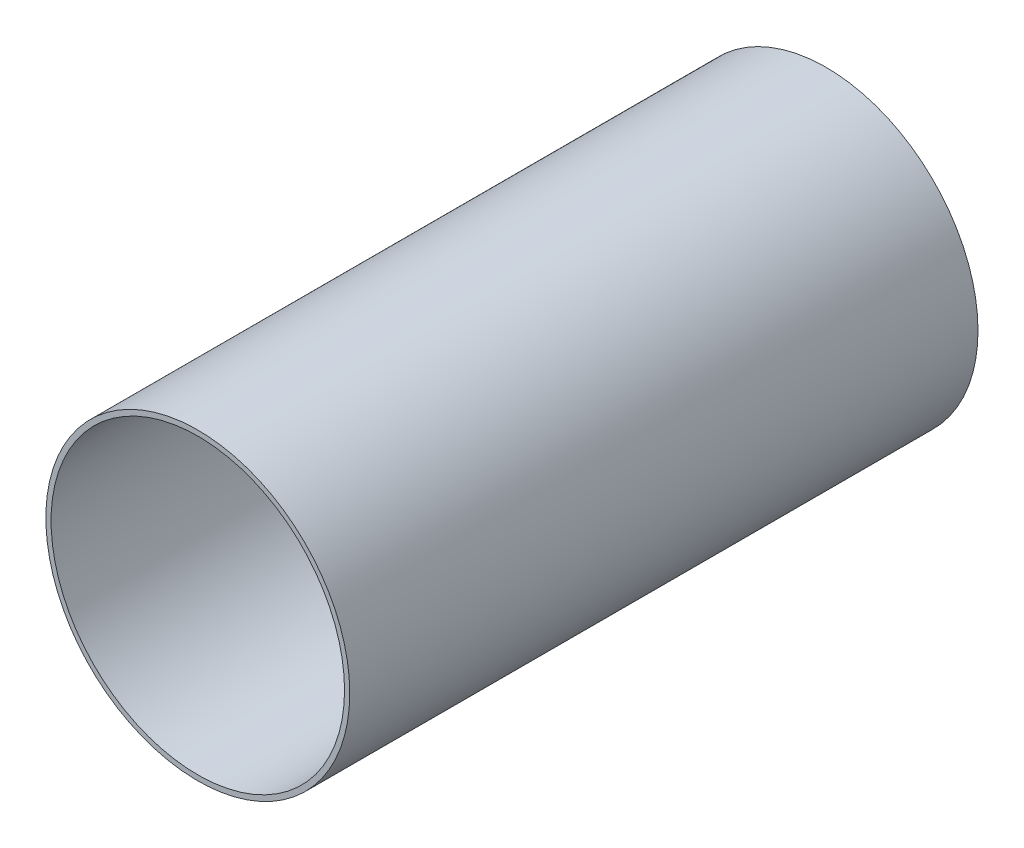
SolidWorks part; units mm, degrees
material "ABS"
ref_plane "Ebene vorne" through (0, 0, 0) normal (0, 0, 1) x (1, 0, 0)
ref_plane "Ebene oben" through (0, 0, 0) normal (0, 1, 0) x (1, 0, 0)
ref_plane "Ebene rechts" through (0, 0, 0) normal (1, 0, 0) x (0, 0, -1)
sketch "Sketch1" plane through (0, 0, 0) normal (0, 0, 1) x (1, 0, 0)
  circle A0 centre (0, 0) radius 76.29
  circle A1 centre (0, 0) radius 79
  dimension "D1" = 152.58
  dimension "D2" = 158
extrude "Boss-Extrude1" add sketch "Sketch1" along normal blind 326.63
